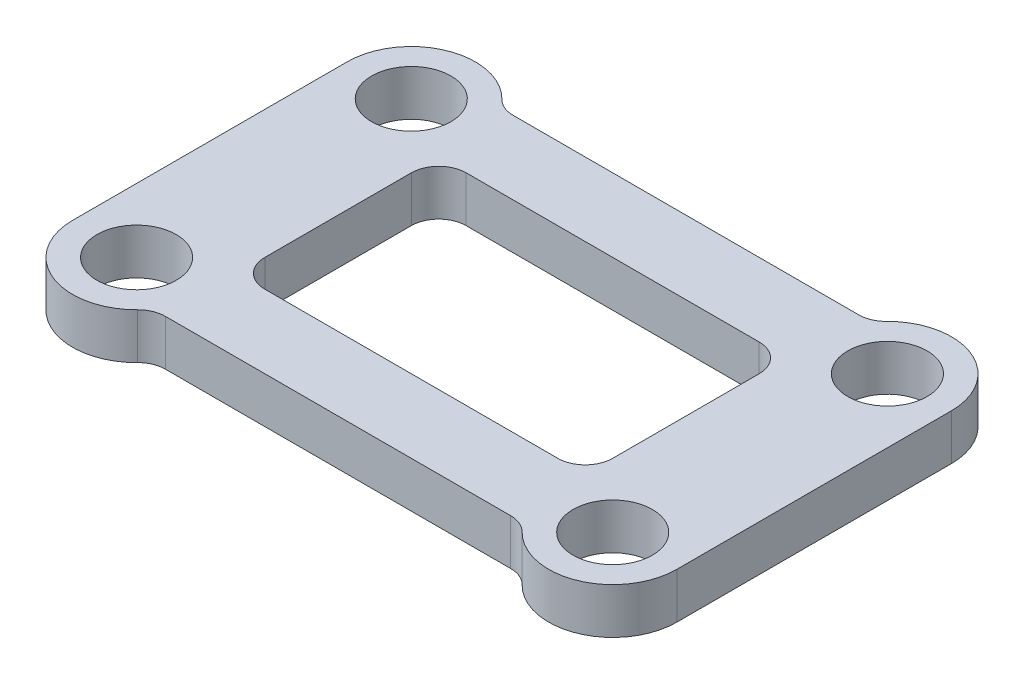
SolidWorks part; units mm, degrees
material "6061-T6 (SS)"
ref_plane "Front Plane" through (0, 0, 0) normal (0, 0, 1) x (1, 0, 0)
ref_plane "Top Plane" through (0, 0, 0) normal (0, 1, 0) x (1, 0, 0)
ref_plane "Right Plane" through (0, 0, 0) normal (1, 0, 0) x (0, 0, -1)
sketch "Sketch1" plane through (0, -19.05, 0) normal (0, -1, 0) x (1, 0, 0)
  line L0 (-29.21, 9.525) -> (-29.21, -9.525) construction
  line L5 (-24.765, 9.525) -> (-24.765, -9.525)
  line L6 (-33.655, 9.525) -> (-33.655, -9.525)
  line L7 (3.81, 9.525) -> (3.81, -9.525) construction
  line L8 (8.255, 9.525) -> (8.255, -9.525)
  line L9 (-0.635, 9.525) -> (-0.635, -9.525)
  arc A4 (-24.765, 9.525) -> (-33.655, 9.525) centre (-29.21, 9.525) ccw
  arc A5 (-33.655, -9.525) -> (-24.765, -9.525) centre (-29.21, -9.525) ccw
  arc A6 (8.255, 9.525) -> (-0.635, 9.525) centre (3.81, 9.525) ccw
  arc A7 (-0.635, -9.525) -> (8.255, -9.525) centre (3.81, -9.525) ccw
  point P2 (-29.21, 0)
  point P12 (3.81, 0)
  dimension "D1" = 4.445
  dimension "D2" = 4.445
extrude "Boss-Extrude2" add sketch "Sketch1" along normal blind 3.175
sketch "Sketch7" plane through (0, -22.225, 0) normal (0, -1, 0) x (1, 0, 0)
  line L0 (-29.21, 9.525) -> (3.81, 9.525)
  line L2 (-29.21, -9.525) -> (3.81, -9.525)
  point P3 (-28.8997, -9.525)
  point P6 (4.2604, 9.5095)
  point P8 (0, 0)
  point P9 (-29.21, -5.9742)
extrude "Extrude-Thin1" add sketch "Sketch7" against normal up to surface (3.175 mm away) thin up to face at (-29.21, -19.05, 0) thin type mid plane wall 5.08
hole_wizard "M5 Clearance Hole1" positions "3DSketch1" profile "Sketch5" hole size "M5" standard "ANSI Metric" end condition through all
sketch3d "3DSketch1"
  line L0 (-29.21, -22.225, 9.525) -> (-29.21, -19.05, 9.525) construction
  line L1 (-29.21, -22.225, -9.525) -> (-29.21, -19.05, -9.525) construction
  line L2 (3.81, -22.225, 9.525) -> (3.81, -19.05, 9.525) construction
  line L3 (3.81, -22.225, -9.525) -> (3.81, -19.05, -9.525) construction
  point P0 (-29.21, -22.225, 9.525)
  point P4 (-29.21, -22.225, -9.525)
  point P8 (3.81, -22.225, 9.525)
  point P12 (3.81, -22.225, -9.525)
sketch "Sketch5" plane through (-29.21, -22.225, 9.525) normal (1, 0, 0) x (0, 0, -1)
  line L0 (0, 0) -> (0, 3.175)
  line L1 (0, 3.175) -> (2.75, 3.175)
  line L2 (2.75, 3.175) -> (2.75, 0)
  line L5 (2.75, 0) -> (0, 0)
  line L11 (0, -6.35) -> (0, 107.95) construction
  dimension "Thru Hole Dia." = 5.5
  dimension "Thru Hole Depth" = 3.175
fillet "Fillet1" radius 1.905 8 edges at (-25.5622, -20.6375, -12.065) (0.1622, -20.6375, -12.065) (-0.635, -20.6375, -6.985) (-24.765, -20.6375, 6.985) (0.1622, -20.6375, 12.065) (-25.5622, -20.6375, 12.065) (-0.635, -20.6375, 6.985) (-24.765, -20.6375, -6.985)
